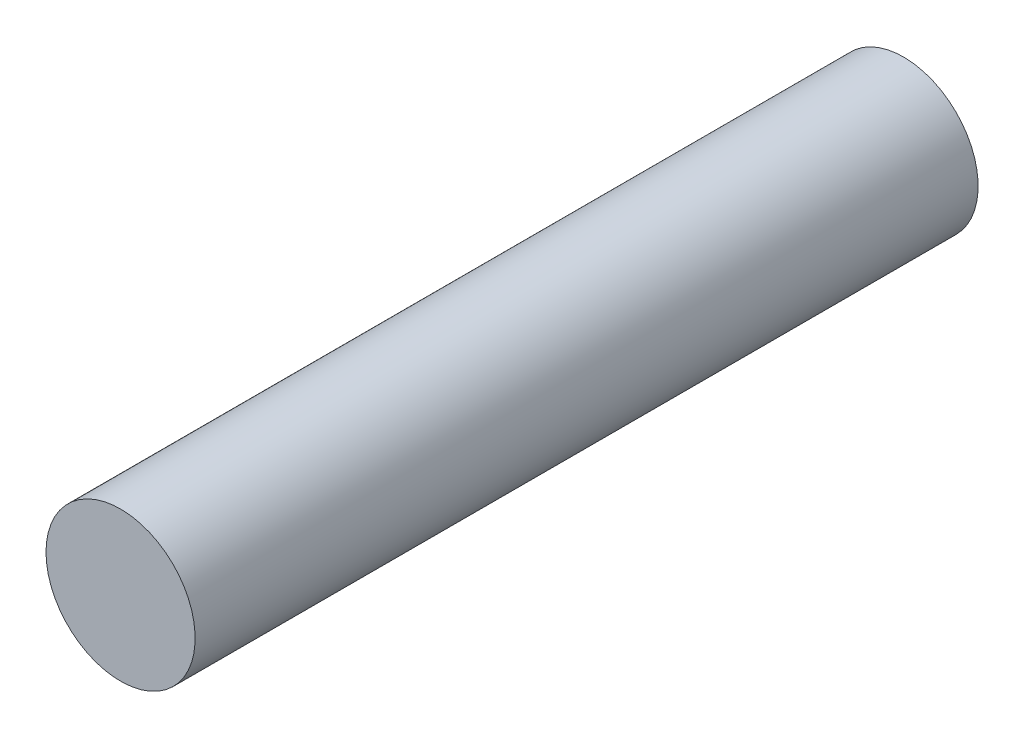
SolidWorks part; units mm, degrees
ref_plane "Front Plane" through (0, 0, 0) normal (0, 0, 1) x (1, 0, 0)
ref_plane "Top Plane" through (0, 0, 0) normal (0, 1, 0) x (1, 0, 0)
ref_plane "Right Plane" through (0, 0, 0) normal (1, 0, 0) x (0, 0, -1)
sketch "Sketch1" plane through (0, 0, 0) normal (0, 0, 1) x (1, 0, 0)
  circle A0 centre (0, 0) radius 4
  dimension "D1" = 8
extrude "Boss-Extrude1" add sketch "Sketch1" along normal mid plane 42
